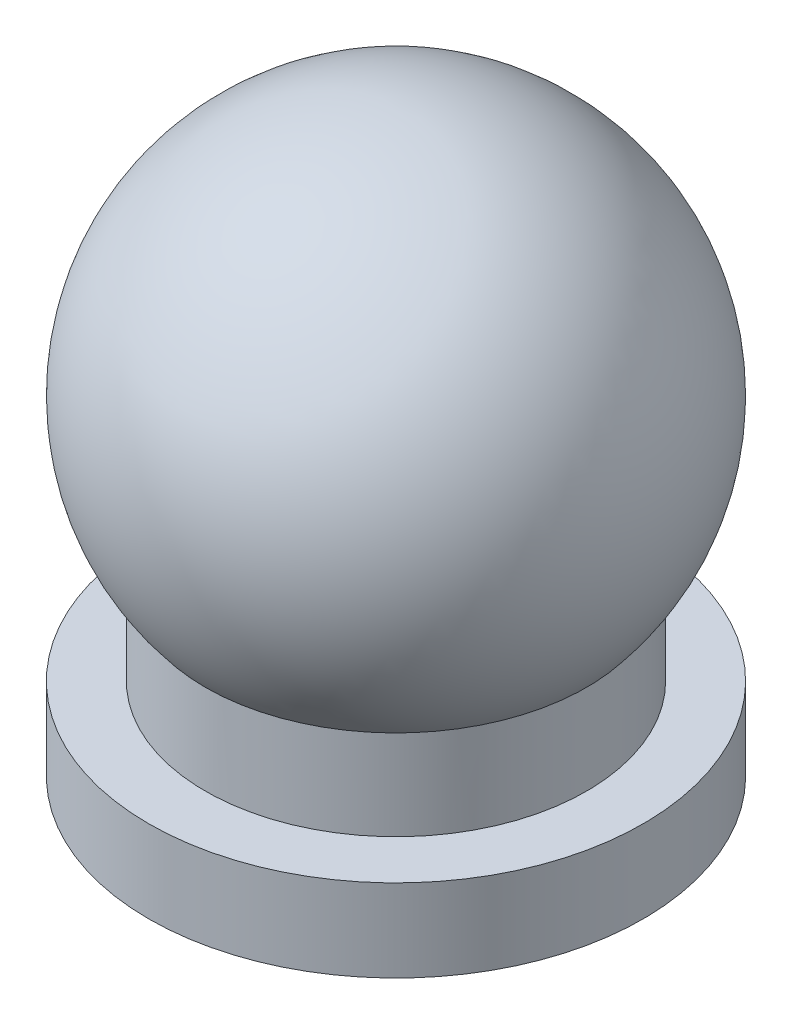
SolidWorks part; units mm, degrees
ref_plane "Front Plane" through (0, 0, 0) normal (0, 0, 1) x (1, 0, 0)
ref_plane "Top Plane" through (0, 0, 0) normal (0, 1, 0) x (1, 0, 0)
ref_plane "Right Plane" through (0, 0, 0) normal (1, 0, 0) x (0, 0, -1)
sketch "Sketch1" plane through (0, 0, 0) normal (0, 1, 0) x (1, 0, 0)
  circle A0 centre (0, 0) radius 3
  dimension "D1" = 6
extrude "Boss-Extrude1" add sketch "Sketch1" along normal blind 1
sketch "Sketch3" plane through (0, 0, 0) normal (1, 0, 0) x (0, 0, -1)
  line L5 (0, 1) -> (0, 4)
  line L6 (3, 1) -> (-3, 1) construction
  line L8 (0, 1) -> (-1.1569, 1)
  line L9 (0, 1) -> (-2.3138, 1)
  line L10 (0, 4) -> (0, 7)
  line L12 (-2.3138, 2.0905) -> (-2.3138, 1)
  arc A4 (0, 7) -> (-3, 4) centre (0, 4) ccw
  arc A5 (0, 7) -> (-2.3138, 2.0905) centre (0, 4) ccw
revolve "Revolve2" add sketch "Sketch3" angle 360 about L10
sketch "Sketch4" plane through (0, 0, 0) normal (0, -1, 0) x (1, 0, 0)
  circle A0 centre (0, 0) radius 0.975
extrude "Cut-Extrude1" cut sketch "Sketch4" against normal blind 5.5
